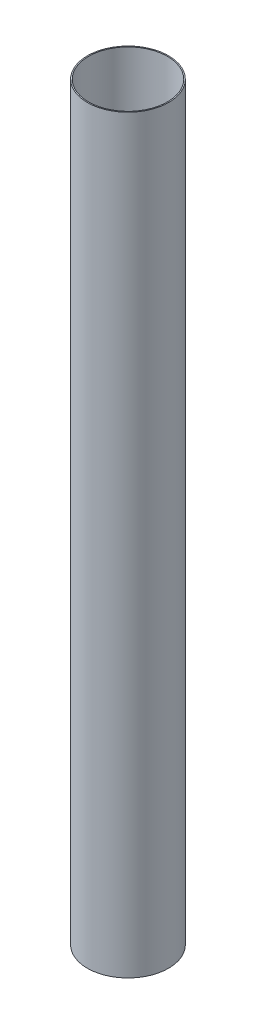
SolidWorks part; units mm, degrees
material "C-Glass Fiber"
ref_plane "Front Plane" through (0, 0, 0) normal (0, 0, 1) x (1, 0, 0)
ref_plane "Top Plane" through (0, 0, 0) normal (0, 1, 0) x (1, 0, 0)
ref_plane "Right Plane" through (0, 0, 0) normal (1, 0, 0) x (0, 0, -1)
other "Configuration Table"
sketch "Sketch1" plane through (0, 0, 0) normal (0, 1, 0) x (1, 0, 0)
  circle A0 centre (0, 0) radius 78.359
  circle A1 centre (0, 0) radius 76.2
  dimension "D1" = 152.4
  dimension "D2" = 156.718
extrude "Boss-Extrude1" add sketch "Sketch1" along normal blind 1447.8
equation "\"OD\"= 6.17"
equation "\"ID\"= 6"
equation "\"D1@Sketch1\"=\"ID\""
equation "\"D2@Sketch1\"=\"OD\""
equation "\"L\"= 57"
equation "\"D1@Boss-Extrude1\"=\"L\""
